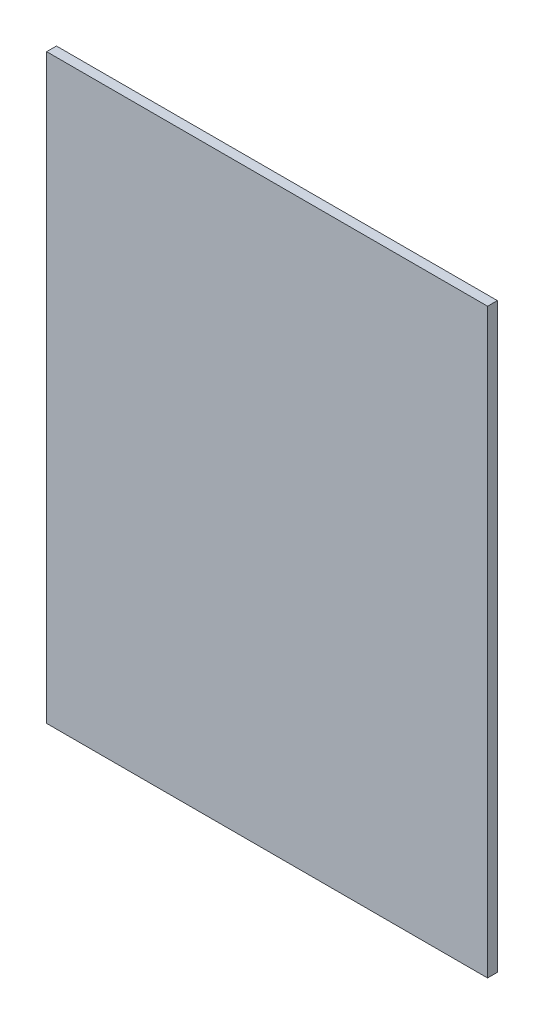
SolidWorks part; units mm, degrees
ref_plane "正面" through (0, 0, 0) normal (0, 0, 1) x (1, 0, 0)
ref_plane "平面" through (0, 0, 0) normal (0, 1, 0) x (1, 0, 0)
ref_plane "右側面" through (0, 0, 0) normal (1, 0, 0) x (0, 0, -1)
sketch "ｽｹｯﾁ1" plane through (0, 0, 0) normal (0, 0, 1) x (1, 0, 0)
  line L1 (-73.8944, 61.9929) -> (-1.8944, 61.9929)
  line L2 (-73.8944, 61.9929) -> (-73.8944, -33.0071)
  line L3 (-73.8944, -33.0071) -> (-1.8944, -33.0071)
  line L4 (-1.8944, 61.9929) -> (-1.8944, -33.0071)
  dimension "D3" = 95
  dimension "D4" = 72
extrude "ﾎﾞｽ - 押し出し1" add sketch "ｽｹｯﾁ1" along normal blind 1.6
